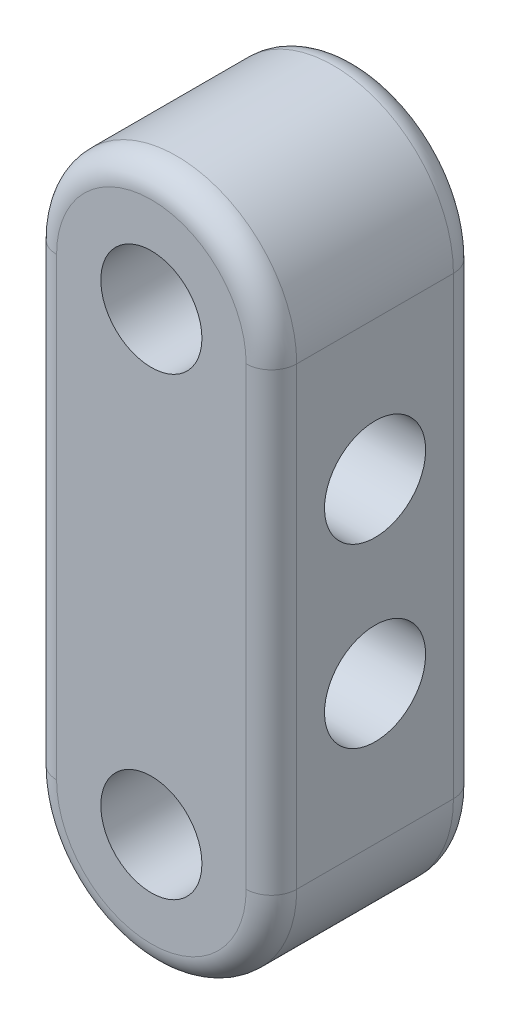
SolidWorks part; units mm, degrees
ref_plane "Face" through (0, 0, 0) normal (0, 0, 1) x (1, 0, 0)
ref_plane "Dessus" through (0, 0, 0) normal (0, 1, 0) x (1, 0, 0)
ref_plane "Droite" through (0, 0, 0) normal (1, 0, 0) x (0, 0, -1)
sketch "Esquisse1" plane through (0, 0, 0) normal (0, 0, 1) x (1, 0, 0)
  line L0 (0, 0) -> (0, 18)
  line L2 (9.5, 18) -> (9.5, 0)
  arc A0 (9.5, 18) -> (0, 18) centre (4.75, 18) ccw
  arc A1 (9.5, 0) -> (0, 0) centre (4.75, 0) cw
  dimension "D1" = 4.75
  dimension "D2" = 18
extrude "Base-Extrusion" add sketch "Esquisse1" along normal blind 8.2
sketch "Esquisse2" plane through (0, 0, 8.2) normal (0, 0, 1) x (1, 0, 0)
  circle A0 centre (4.75, 18) radius 2
  circle A1 centre (4.75, 0) radius 2
  arc A2 (9.5, 18) -> (0, 18) centre (4.75, 18) ccw construction
  arc A3 (0, 0) -> (9.5, 0) centre (4.75, 0) ccw construction
  dimension "D1" = 4
  dimension "D2" = 4
extrude "Enlèv. mat.-Extru.1" cut sketch "Esquisse2" against normal through all
fillet "Congé1" radius 1 4 edges at (4.75, 22.75, 8.2) (0, 9, 8.2) (4.75, -4.75, 8.2) (9.5, 9, 8.2)
fillet "Congé2" radius 1 4 edges at (0, 9, 0) (4.75, 22.75, 0) (9.5, 9, 0) (4.75, -4.75, 0)
sketch "Esquisse3" plane through (9.5, 0, 0) normal (1, 0, 0) x (0, 0, -1)
  line L1 (-8.2, 0) -> (-8.2, 18) construction
  line L2 (0, 18) -> (0, 0) construction
  line L4 (-4.1, 5.5) -> (-4.1, 12.5) construction
  line L5 (-9.5074, 9) -> (1.3074, 9) construction
  circle A0 centre (-4.1, 12.5) radius 2
  circle A1 centre (-4.1, 5.5) radius 2
  point P2 (-8.2, 9)
  point P3 (-4.1, 9)
  dimension "D4" = 4
  dimension "D5" = 4
  dimension "D2" = 4.1
  dimension "D3" = 7
  dimension "D6" = 4.1
extrude "Enlèv. mat.-Extru.2" cut sketch "Esquisse3" against normal through all
